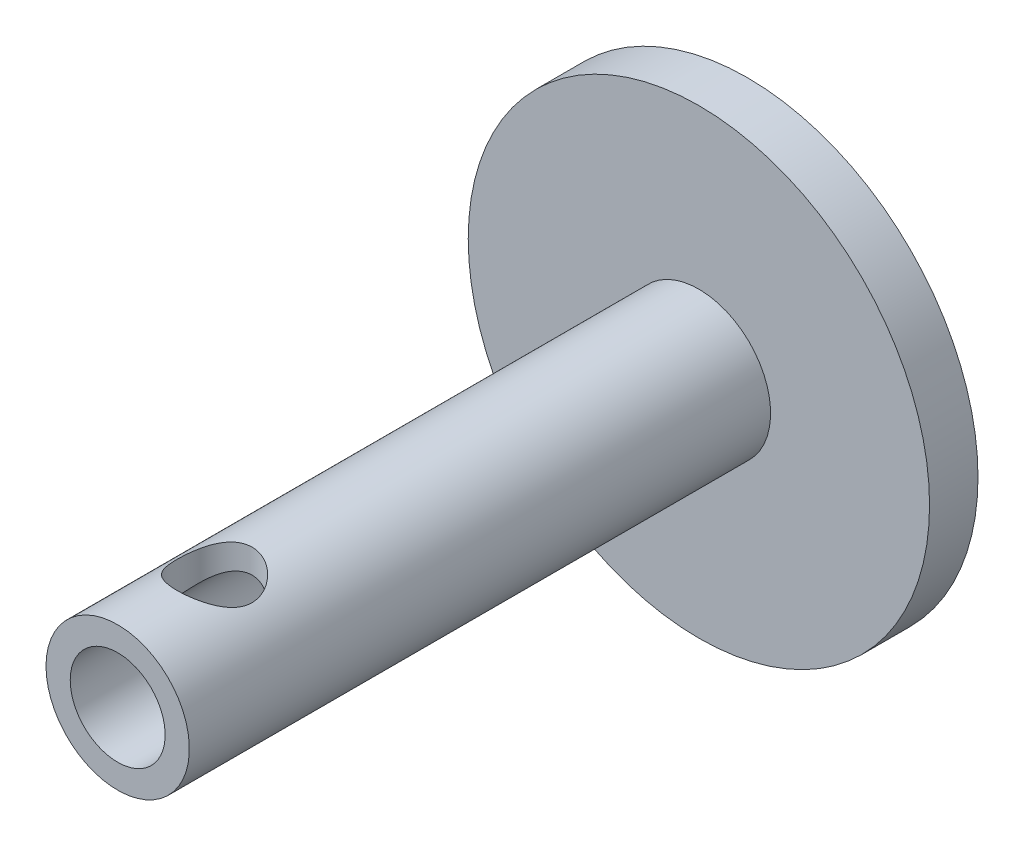
SolidWorks part; units mm, degrees
ref_plane "Front Plane" through (0, 0, 0) normal (0, 0, 1) x (1, 0, 0)
ref_plane "Top Plane" through (0, 0, 0) normal (0, 1, 0) x (1, 0, 0)
ref_plane "Right Plane" through (0, 0, 0) normal (1, 0, 0) x (0, 0, -1)
sketch "Sketch1" plane through (0, 0, 0) normal (0, 1, 0) x (1, 0, 0)
  line L0 (1.96, -24) -> (1.96, 0)
  line L1 (0, 0) -> (1.96, 0)
  line L2 (9.525, 0) -> (9.525, 2)
  line L3 (9.525, 2) -> (0, 2)
  line L4 (0, 2) -> (0, 0)
  line L5 (2.96, 0) -> (2.96, -24)
  line L6 (2.96, -24) -> (1.96, -24)
  line L7 (2.96, 0) -> (9.525, 0)
  dimension "D1" = 1
  dimension "D2" = 24
  dimension "D3" = 2.96
  dimension "D4" = 9.525
  dimension "D5" = 2
revolve "Revolve1" add sketch "Sketch1" angle 360 about L4
ref_plane "Plane1" through (0, 2.96, 0) normal (0, 1, 0) x (1, 0, 0)
sketch "Sketch4" plane through (0, 2.96, 0) normal (0, 1, 0) x (1, 0, 0)
  circle A0 centre (0, -20) radius 0.5
  point P0 (0, -20)
  dimension "D1" = 1
  dimension "D2" = 20
hole_wizard "M2.5 Clearance Hole1" positions "Sketch4" profile "Sketch5" hole size "M2.5" standard "ISO" end condition through all
sketch "Sketch5" plane through (0, 2.96, 20) normal (1, 0, 0) x (0, 0, 1)
  line L0 (0, 0) -> (0, 12.485)
  line L1 (0, 12.485) -> (1.55, 12.485)
  line L2 (1.55, 12.485) -> (1.55, 0)
  line L5 (1.55, 0) -> (0, 0)
  line L11 (0, -6.35) -> (0, 107.95) construction
  dimension "Thru Hole Dia." = 3.1
  dimension "Thru Hole Depth" = 12.485
